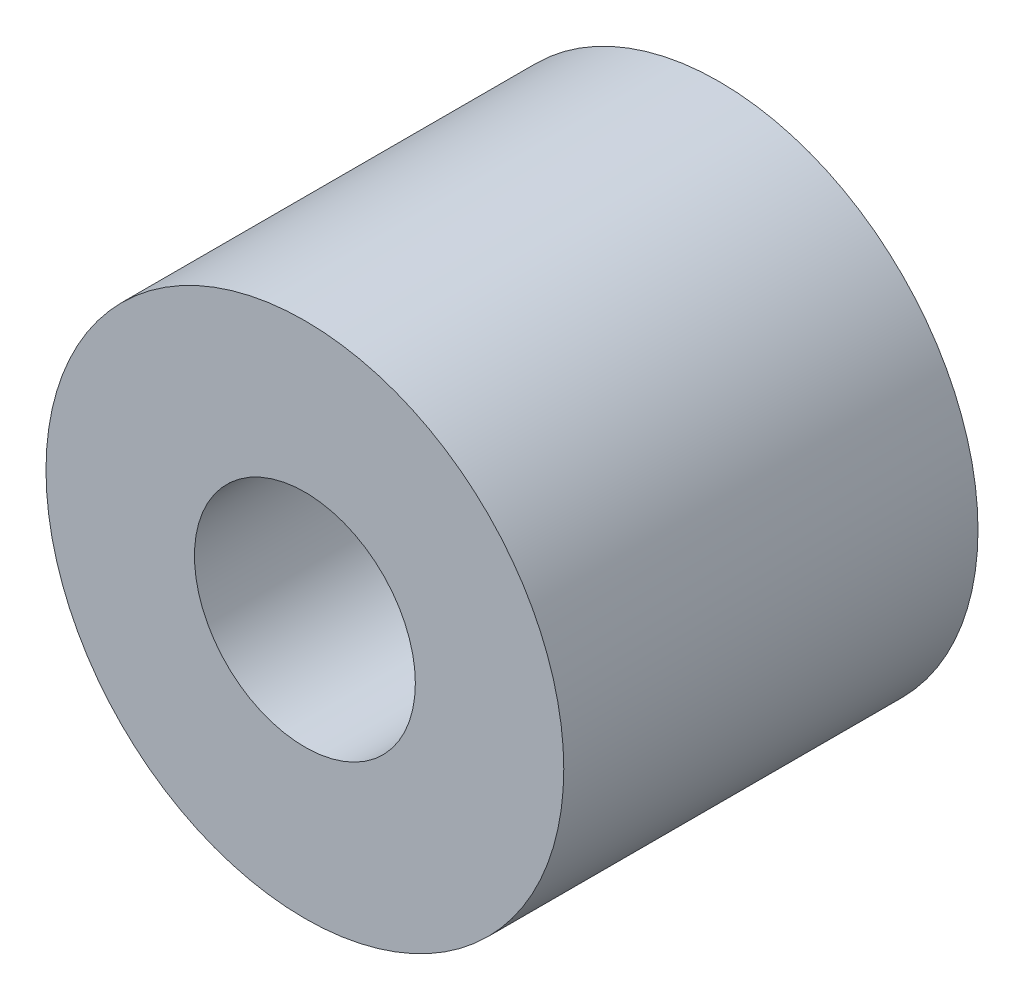
SolidWorks part; units mm, degrees
ref_plane "정면" through (0, 0, 0) normal (0, 0, 1) x (1, 0, 0)
ref_plane "윗면" through (0, 0, 0) normal (0, 1, 0) x (1, 0, 0)
ref_plane "우측면" through (0, 0, 0) normal (1, 0, 0) x (0, 0, -1)
sketch "스케치1" plane through (0, 0, 0) normal (0, 0, 1) x (1, 0, 0)
  circle A0 centre (0, 0) radius 3.2
  circle A1 centre (0, 0) radius 7.5
  dimension "D1" = 6.4
  dimension "D2" = 15
extrude "보스-돌출1" add sketch "스케치1" along normal blind 12
